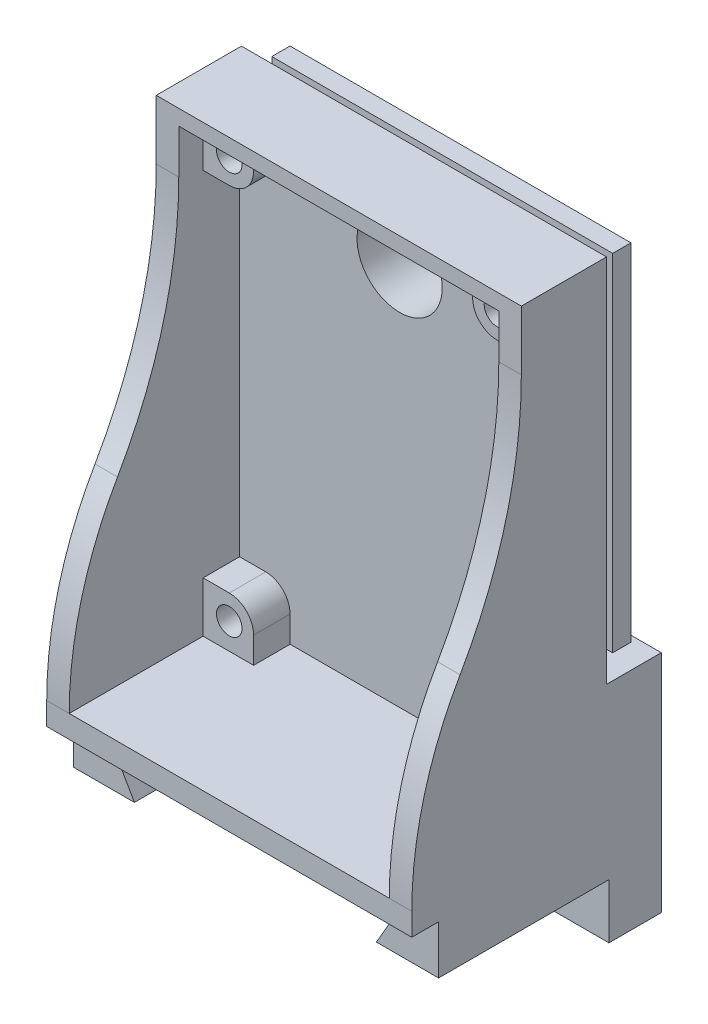
SolidWorks part; units mm, degrees
ref_plane "Front Plane" through (0, 0, 0) normal (0, 0, 1) x (1, 0, 0)
ref_plane "Top Plane" through (0, 0, 0) normal (0, 1, 0) x (1, 0, 0)
ref_plane "Right Plane" through (0, 0, 0) normal (1, 0, 0) x (0, 0, -1)
sketch "pcb" plane through (0, 0, 0) normal (0, 0, 1) x (1, 0, 0)
  line L0 (0, 2) -> (2, 2) construction
  line L1 (0, 0) -> (26, 0) construction
  line L2 (0, 0) -> (0, 37) construction
  line L3 (0, 37) -> (26, 37) construction
  line L4 (26, 0) -> (26, 37) construction
  line L5 (2, 2) -> (2, 0) construction
  line L6 (26, 2) -> (24, 2) construction
  line L7 (24, 2) -> (24, 0) construction
  line L8 (2, 37) -> (2, 35) construction
  line L9 (2, 35) -> (0, 35) construction
  line L10 (24, 37) -> (24, 35) construction
  line L11 (24, 35) -> (26, 35) construction
  circle A0 centre (2, 35) radius 1.05 construction
  circle A1 centre (24, 35) radius 1.05 construction
  circle A2 centre (24, 2) radius 1.05 construction
  circle A3 centre (2, 2) radius 1.05 construction
  circle A4 centre (13, 31.463) radius 2.964 construction
  point P23 (13, 37)
  dimension "D3" = 2.1
  dimension "D6" = 5.928
  dimension "D1" = 37
  dimension "D2" = 26
  dimension "D4" = 2
  dimension "D5" = 31.463
sketch "Sketch2" plane through (0, 0, 0) normal (0, 0, 1) x (1, 0, 0)
  line L0 (0, 0) -> (-2, 0) construction
  line L1 (-2, 8) -> (28, 8)
  line L2 (-2, 8) -> (-2, -10.5)
  line L3 (-2, -10.5) -> (28, -10.5)
  line L4 (28, 8) -> (28, -10.5)
  line L5 (26, 0) -> (28, 0) construction
  line L6 (0, 0) -> (26, 0) construction
  dimension "D1" = 2
  dimension "D2" = 8
  dimension "D3" = 10.5
extrude "Boss-Extrude1" add sketch "Sketch2" along normal blind 4.5
sketch "Sketch3" plane through (0, 0, 4.5) normal (0, 0, 1) x (1, 0, 0)
  line L0 (0, 0) -> (26, 0) construction
  line L1 (-2, 38.4159) -> (28, 38.4159)
  line L2 (-2, 38.4159) -> (-2, -6)
  line L4 (28, 38.4159) -> (28, -6)
  line L6 (28, -10.5) -> (28, 8) construction
  line L7 (-2, 8) -> (-2, -10.5) construction
  line L8 (-2, -6) -> (3.0094, -6)
  line L9 (3.0094, -6) -> (0.7, -2)
  line L10 (0.7, -2) -> (25.2, -2)
  line L11 (25.2, -2) -> (22.8906, -6)
  line L12 (22.8906, -6) -> (28, -6)
  dimension "D1" = 60
  dimension "D2" = 60
  dimension "D3" = 2.7
  dimension "D4" = 4
  dimension "D5" = 2.8
  dimension "D6" = 2
extrude "Boss-Extrude2" add sketch "Sketch3" along normal blind 2
sketch "Sketch4" plane through (0, 0, 6.5) normal (0, 0, 1) x (1, 0, 0)
  line L0 (0, 18.5) -> (-0.15, 18.5) construction
  line L1 (-0.15, 37.15) -> (26.15, 37.15)
  line L2 (-0.15, 37.15) -> (-0.15, -0.15)
  line L3 (-0.15, -0.15) -> (26.15, -0.15)
  line L4 (26.15, 37.15) -> (26.15, -0.15)
  line L5 (0, 0) -> (0, 37) construction
  line L6 (13, 37) -> (13, 37.15) construction
  line L7 (0, 37) -> (26, 37) construction
  line L8 (-2, 38.4159) -> (-2, -6)
  line L9 (-2, -6) -> (3.0094, -6)
  line L10 (3.0094, -6) -> (0.7, -2)
  line L11 (0.7, -2) -> (25.2, -2)
  line L12 (25.2, -2) -> (22.8906, -6)
  line L13 (22.8906, -6) -> (28, -6)
  line L14 (28, -6) -> (28, 38.4159)
  line L15 (28, 38.4159) -> (-2, 38.4159)
  line L16 (-2, 38.4159) -> (-2, -6)
  line L17 (-2, -6) -> (3.0094, -6)
  line L18 (3.0094, -6) -> (0.7, -2)
  line L19 (0.7, -2) -> (25.2, -2)
  line L20 (25.2, -2) -> (22.8906, -6)
  line L21 (22.8906, -6) -> (28, -6)
  line L22 (28, -6) -> (28, 38.4159)
  line L23 (28, 38.4159) -> (-2, 38.4159)
  dimension "D2" = 0.15
  dimension "D1" = 0
extrude "Boss-Extrude3" add sketch "Sketch4" along normal blind 12
sketch "Sketch5" plane through (0, 0, 18.5) normal (0, 0, 1) x (1, 0, 0)
  line L0 (28, -6) -> (28, 38.4159) construction
  line L1 (-2, 38.4159) -> (28, 38.4159)
  line L2 (-2, 38.4159) -> (-2, -2)
  line L3 (-2, -2) -> (28, -2)
  line L4 (28, 38.4159) -> (28, -2)
  line L5 (0.7, -2) -> (25.2, -2) construction
  line L6 (26.15, -0.15) -> (-0.15, -0.15)
  line L7 (26.15, -0.15) -> (26.15, 37.15)
  line L8 (26.15, 37.15) -> (-0.15, 37.15)
  line L9 (-0.15, -0.15) -> (-0.15, 37.15)
extrude "Boss-Extrude4" add sketch "Sketch5" along normal blind 2
sketch "Sketch6" plane through (28, 0, 0) normal (1, 0, 0) x (0, 0, -1)
  line L0 (-20.5, -2) -> (-20.5, 38.4159) construction
  line L1 (-11.5, 38.4159) -> (-29.9203, 38.4159)
  line L2 (-11.5, 33.5206) -> (-11.5, 38.4159)
  line L3 (-20.5, 38.4159) -> (-4.5, 38.4159) construction
  line L4 (-6.5, -0.15) -> (-6.5, 37.15) construction
  line L8 (-20.5, -0.15) -> (-29.9203, -0.15)
  line L9 (-29.9203, -0.15) -> (-29.9203, 38.4159)
  arc A0 (-16.5317, 14.696) -> (-20.5, -0.15) centre (9.2549, -0.15) ccw
  arc A2 (-16.5317, 14.696) -> (-11.5, 33.5206) centre (-49.2291, 33.5206) ccw
  dimension "D1" = 5
extrude "Cut-Extrude1" cut sketch "Sketch6" against normal through all
sketch "Sketch7" plane through (0, 0, 0) normal (0, 0, -1) x (-1, 0, 0)
  line L0 (2, -10.5) -> (-28, -10.5) construction
  line L1 (-13, -9) -> (-13, 49991) construction
  circle A0 centre (-19.5, -6.25) radius 2.75
  circle A1 centre (-6.5, -6.25) radius 2.75
  point P4 (-13, -10.5)
  dimension "D2" = 5.5
  dimension "D1" = 4.25
  dimension "D3" = 6.5
extrude "Cut-Extrude2" cut sketch "Sketch7" against normal blind 3
sketch "Sketch8" plane through (0, 0, 3) normal (0, 0, -1) x (-1, 0, 0)
  circle A0 centre (-19.5, -6.25) radius 1.65
  circle A1 centre (-19.5, -6.25) radius 2.75 construction
  circle A2 centre (-19.5, -6.25) radius 2.75 construction
  circle A3 centre (-6.5, -6.25) radius 2.75 construction
  circle A4 centre (-6.5, -6.25) radius 2.75 construction
  circle A5 centre (-6.5, -6.25) radius 1.65
  dimension "D1" = 3.3
extrude "Cut-Extrude3" cut sketch "Sketch8" against normal through all
sketch "Sketch9" plane through (-2, 0, 0) normal (-1, 0, 0) x (0, 0, 1)
  line L0 (18.5, -6) -> (4.5, -6) construction
  line L1 (18.3, -6) -> (18.5, -6)
  line L2 (18.3, -6) -> (18.3, -2)
  line L3 (18.3, -2) -> (18.5, -2)
  line L4 (18.5, -6) -> (18.5, -2)
  dimension "D1" = 0.2
extrude "tolerance_cut1" cut sketch "Sketch9" against normal through all
sketch "Sketch10" plane through (0, 0, 4.5) normal (0, 0, 1) x (1, 0, 0)
  line L8 (28, -6) -> (22.8906, -6)
  line L9 (22.8906, -6) -> (25.2, -2)
  line L10 (25.2, -2) -> (0.7, -2)
  line L11 (0.7, -2) -> (3.0094, -6)
  line L12 (3.0094, -6) -> (-2, -6)
  line L13 (-2, -6) -> (-2, -10.5)
  line L14 (-2, -10.5) -> (28, -10.5)
  line L15 (28, -10.5) -> (28, -6)
  line L16 (28, -6) -> (22.8906, -6)
  line L17 (22.8906, -6) -> (25.2, -2)
  line L18 (25.2, -2) -> (0.7, -2)
  line L19 (0.7, -2) -> (3.0094, -6)
  line L20 (3.0094, -6) -> (-2, -6)
  line L21 (-2, -6) -> (-2, -10.5)
  line L22 (-2, -10.5) -> (28, -10.5)
  line L23 (28, -10.5) -> (28, -6)
  dimension "D1" = 0
extrude "tolerance_cut2" cut sketch "Sketch10" against normal blind 0.2
sketch "Sketch11" plane through (0, 0, 6.5) normal (0, 0, 1) x (1, 0, 0)
  line L0 (4, 35) -> (4, 37.15)
  line L1 (-0.15, 37.15) -> (26.15, 37.15) construction
  line L2 (4, 37.15) -> (-0.15, 37.15)
  line L3 (-0.15, 37.15) -> (-0.15, 33)
  line L4 (-0.15, 14.696) -> (-0.15, 33.5206) construction
  line L5 (-0.15, 33) -> (2, 33)
  line L6 (13, 37) -> (13, 0) construction
  line L7 (0, 37) -> (26, 37) construction
  line L8 (0, 0) -> (26, 0) construction
  line L9 (13, 18.5) -> (26, 18.5) construction
  line L10 (26, 0) -> (26, 37) construction
  line L11 (26.15, 33) -> (24, 33)
  line L12 (26.15, 37.15) -> (26.15, 33)
  line L13 (22, 37.15) -> (26.15, 37.15)
  line L14 (22, 35) -> (22, 37.15)
  line L15 (26.15, 4) -> (24, 4)
  line L16 (26.15, -0.15) -> (26.15, 4)
  line L17 (22, -0.15) -> (26.15, -0.15)
  line L18 (22, 2) -> (22, -0.15)
  line L19 (-0.15, 4) -> (2, 4)
  line L20 (-0.15, -0.15) -> (-0.15, 4)
  line L21 (4, -0.15) -> (-0.15, -0.15)
  line L22 (4, 2) -> (4, -0.15)
  arc A0 (2, 33) -> (4, 35) centre (2, 35) ccw
  arc A5 (24, 33) -> (22, 35) centre (24, 35) cw
  arc A6 (24, 4) -> (22, 2) centre (24, 2) ccw
  arc A7 (2, 4) -> (4, 2) centre (2, 2) cw
  dimension "D1" = 4
extrude "Boss-Extrude5" add sketch "Sketch11" along normal blind 3
sketch "Sketch12" plane through (0, 0, 4.5) normal (0, 0, -1) x (-1, 0, 0)
  line L0 (2, 38.4159) -> (2, 8) construction
  line L1 (-26.0111, 36.427) -> (0.0111, 36.427)
  line L2 (-26.0111, 36.427) -> (-26.0111, 9.9889)
  line L3 (-26.0111, 9.9889) -> (0.0111, 9.9889)
  line L4 (0.0111, 36.427) -> (0.0111, 9.9889)
  line L5 (-28, 38.4159) -> (2, 38.4159) construction
  line L6 (-13, 38.4159) -> (-13, 36.427) construction
  line L7 (-26.0111, 23.208) -> (-28, 23.208) construction
  line L8 (-28, 8) -> (-28, 38.4159) construction
  line L9 (-13, 34.427) -> (-13, 36.427) construction
  circle A0 centre (-13, 31.463) radius 2.964 construction
  point P6 (2, 23.208)
  point P7 (0.0111, 23.208)
  point P10 (-13, 38.4159)
  point P11 (-13, 36.427)
  dimension "D1" = 2
extrude "Boss-Extrude6" add sketch "Sketch12" along normal blind 1.5
sketch "Sketch13" plane through (0, 0, 3) normal (0, 0, -1) x (-1, 0, 0)
  line L0 (0.0111, 36.427) -> (-26.0111, 36.427) construction
  line L1 (-27.0055, 37.4215) -> (1.0055, 37.4215)
  line L2 (-27.0055, 37.4215) -> (-27.0055, 8.9945)
  line L3 (-27.0055, 8.9945) -> (1.0055, 8.9945)
  line L4 (1.0055, 37.4215) -> (1.0055, 8.9945)
  line L5 (-26.0111, 36.427) -> (-26.0111, 9.9889) construction
  line L6 (-27.0055, 23.208) -> (-26.0111, 23.208) construction
  line L7 (-26.0111, 36.427) -> (-26.0111, 9.9889) construction
  line L8 (-13, 36.427) -> (-13, 37.4215) construction
  line L9 (-27.0055, 23.208) -> (-28, 23.208) construction
  line L10 (-28, 8) -> (-28, 38.4159) construction
  point P6 (-13, 36.427)
  point P7 (-13, 37.4215)
  point P10 (-26.0111, 23.208)
  point P11 (-27.0055, 23.208)
  dimension "D1" = 0.9945
extrude "Boss-Extrude7" add sketch "Sketch13" along normal blind 1.5
sketch "Sketch14" plane through (0, 0, 6.5) normal (0, 0, 1) x (1, 0, 0)
  circle A0 centre (13, 31.463) radius 3.5
  dimension "D1" = 7
extrude "Cut-Extrude6" cut sketch "Sketch14" against normal through all
sketch "Sketch15" plane through (0, 0, 9.5) normal (0, 0, 1) x (1, 0, 0)
  circle A0 centre (2, 35) radius 1.05
  circle A1 centre (24, 35) radius 1.05
  circle A2 centre (24, 2) radius 1.05
  circle A3 centre (2, 2) radius 1.05
  dimension "D1" = 2.1
extrude "pcb_mount_holes" cut sketch "Sketch15" against normal blind 5
sketch "Sketch16" plane through (0, 0, 1.5) normal (0, 0, -1) x (-1, 0, 0)
  line L0 (0.0111, 36.427) -> (-26.0111, 36.427) construction
  line L1 (-26.0111, 36.427) -> (-26.0111, 9.9889) construction
  line L2 (0.0111, 36.427) -> (-26.0111, 36.427) construction
  line L3 (-26.0111, 36.427) -> (-26.0111, 9.9889) construction
  line L4 (-26.0111, 9.9889) -> (0.0111, 9.9889) construction
  line L5 (0.0111, 9.9889) -> (0.0111, 36.427) construction
  line L6 (-26.0111, 9.9889) -> (0.0111, 9.9889) construction
  line L7 (0.0111, 9.9889) -> (0.0111, 36.427) construction
  line L8 (-24.5111, 26.1694) -> (-24.5111, 24.6694)
  line L9 (-26.0111, 32.1694) -> (-24.5111, 32.1694)
  line L10 (-26.0111, 32.1694) -> (-26.0111, 30.6694)
  line L11 (-26.0111, 30.6694) -> (-24.5111, 30.6694)
  line L12 (-24.5111, 32.1694) -> (-24.5111, 30.6694)
  line L13 (-26.0111, 26.1694) -> (-26.0111, 24.6694)
  line L14 (-26.0111, 26.1694) -> (-24.5111, 26.1694)
  line L15 (-26.0111, 24.6694) -> (-24.5111, 24.6694)
  line L16 (-24.5111, 20.1694) -> (-24.5111, 18.6694)
  line L17 (-26.0111, 20.1694) -> (-26.0111, 18.6694)
  line L18 (-26.0111, 20.1694) -> (-24.5111, 20.1694)
  line L19 (-26.0111, 18.6694) -> (-24.5111, 18.6694)
  line L20 (-24.5111, 14.1694) -> (-24.5111, 12.6694)
  line L21 (-26.0111, 14.1694) -> (-26.0111, 12.6694)
  line L22 (-26.0111, 14.1694) -> (-24.5111, 14.1694)
  line L23 (-26.0111, 12.6694) -> (-24.5111, 12.6694)
  line L24 (-13, 8.9945) -> (-13, 37.6069) construction
  line L25 (-21.7649, 9.9889) -> (-20.2649, 9.9889)
  line L26 (-21.7649, 9.9889) -> (-21.7649, 11.4889)
  line L27 (-21.7649, 11.4889) -> (-20.2649, 11.4889)
  line L28 (-20.2649, 9.9889) -> (-20.2649, 11.4889)
  line L29 (-20.2649, 36.427) -> (-18.7649, 36.427)
  line L30 (-20.2649, 36.427) -> (-20.2649, 34.927)
  line L31 (-20.2649, 34.927) -> (-18.7649, 34.927)
  line L32 (-18.7649, 36.427) -> (-18.7649, 34.927)
  line L33 (-27.0055, 8.9945) -> (1.0055, 8.9945) construction
  line L34 (-4.2351, 11.4889) -> (-5.7351, 11.4889)
  line L35 (-5.7351, 9.9889) -> (-5.7351, 11.4889)
  line L36 (-4.2351, 9.9889) -> (-5.7351, 9.9889)
  line L37 (-4.2351, 9.9889) -> (-4.2351, 11.4889)
  line L38 (0.0111, 14.1694) -> (-1.4889, 14.1694)
  line L39 (0.0111, 14.1694) -> (0.0111, 12.6694)
  line L40 (0.0111, 12.6694) -> (-1.4889, 12.6694)
  line L41 (-1.4889, 14.1694) -> (-1.4889, 12.6694)
  line L42 (0.0111, 20.1694) -> (-1.4889, 20.1694)
  line L43 (0.0111, 20.1694) -> (0.0111, 18.6694)
  line L44 (0.0111, 18.6694) -> (-1.4889, 18.6694)
  line L45 (-1.4889, 20.1694) -> (-1.4889, 18.6694)
  line L46 (0.0111, 26.1694) -> (-1.4889, 26.1694)
  line L47 (0.0111, 26.1694) -> (0.0111, 24.6694)
  line L48 (0.0111, 24.6694) -> (-1.4889, 24.6694)
  line L49 (-1.4889, 26.1694) -> (-1.4889, 24.6694)
  line L50 (0.0111, 30.6694) -> (-1.4889, 30.6694)
  line L51 (-1.4889, 32.1694) -> (-1.4889, 30.6694)
  line L52 (0.0111, 32.1694) -> (-1.4889, 32.1694)
  line L53 (0.0111, 32.1694) -> (0.0111, 30.6694)
  line L54 (-5.7351, 34.927) -> (-7.2351, 34.927)
  line L55 (-7.2351, 36.427) -> (-7.2351, 34.927)
  line L56 (-5.7351, 36.427) -> (-7.2351, 36.427)
  line L57 (-5.7351, 36.427) -> (-5.7351, 34.927)
  dimension "D1" = 1.5
  dimension "D2" = 4
extrude "Cut-Extrude8" cut sketch "Sketch16" against normal blind 3
